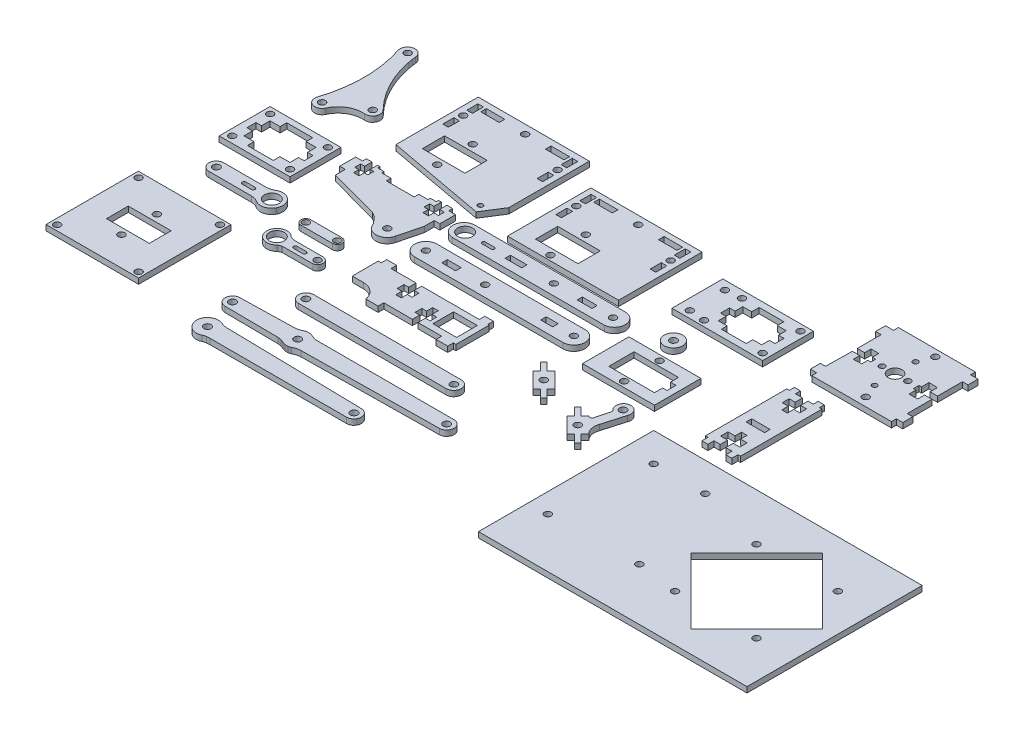
SolidWorks part; units mm, degrees
ref_plane "Front Plane" through (0, 0, 0) normal (0, 0, 1) x (1, 0, 0)
ref_plane "Top Plane" through (0, 0, 0) normal (0, 1, 0) x (1, 0, 0)
ref_plane "Right Plane" through (0, 0, 0) normal (1, 0, 0) x (0, 0, -1)
sketch "Sketch6" plane through (0, 0, -6.8736) normal (0, 1, 0) x (1, 0, 0)
  line L36 (172.3993, 17.524) -> (172.3993, 14.7799)
  line L37 (172.3993, 14.7799) -> (176.2794, 14.7799)
  line L38 (176.2794, 14.7799) -> (176.2794, 10.7799)
  line L39 (176.2794, 10.7799) -> (173.032, 10.7799)
  line L40 (173.032, 10.7799) -> (173.032, 7.063)
  line L41 (173.032, 7.063) -> (176.2794, 7.063)
  line L42 (176.2794, 7.063) -> (176.2794, 3.563)
  line L43 (176.2794, 3.563) -> (179.2794, 3.563)
  line L44 (179.2794, 3.563) -> (179.2794, 7.063)
  line L45 (179.2794, 7.063) -> (182.5439, 7.063)
  line L46 (182.5439, 7.063) -> (182.5439, 10.7799)
  line L47 (182.5439, 10.7799) -> (179.2794, 10.7799)
  line L48 (179.2794, 10.7799) -> (179.2794, 14.7799)
  line L49 (179.2794, 14.7799) -> (182.1277, 14.7799)
  line L50 (182.1277, 14.7799) -> (182.1277, 17.4216)
  line L54 (182.1277, -32.5784) -> (182.1277, -29.2201)
  line L55 (182.1277, -29.2201) -> (178.7635, -29.2201)
  line L56 (178.7635, -29.2201) -> (178.7635, -25.2201)
  line L57 (178.7635, -25.2201) -> (182.3404, -25.2201)
  line L58 (182.3404, -25.2201) -> (182.3404, -21.2526)
  line L59 (182.3404, -21.2526) -> (178.7635, -21.2526)
  line L60 (178.7635, -21.2526) -> (178.7635, -17.7526)
  line L61 (178.7635, -17.7526) -> (175.7635, -17.7526)
  line L62 (175.7635, -17.7526) -> (175.7635, -21.2526)
  line L63 (175.7635, -21.2526) -> (171.9828, -21.2526)
  line L64 (171.9828, -21.2526) -> (171.9828, -25.2201)
  line L65 (171.9828, -25.2201) -> (175.7635, -25.2201)
  line L66 (175.7635, -25.2201) -> (175.7635, -29.2201)
  line L67 (175.7635, -29.2201) -> (172.3993, -29.2201)
  line L68 (172.3993, -29.2201) -> (172.3993, -32.476)
  line L72 (172.2635, -8.7201) -> (182.2635, -8.7201)
  line L73 (182.2635, -8.7201) -> (182.2635, -11.7201)
  line L74 (182.2635, -11.7201) -> (172.2635, -11.7201)
  line L75 (172.2635, -11.7201) -> (172.2635, -8.7201)
  line L132 (186.7635, -29.2201) -> (185.3957, -29.2201)
  line L133 (185.3957, -29.2201) -> (185.3957, -32.5784)
  line L134 (167.7635, -29.2201) -> (169.1313, -29.2201)
  line L135 (169.1313, -29.2201) -> (169.1313, -32.476)
  line L136 (169.1313, 17.524) -> (169.1313, 14.7799)
  line L137 (169.1313, 14.7799) -> (167.7635, 14.7799)
  line L138 (185.3957, 17.4216) -> (185.3957, 14.7799)
  line L139 (185.3957, 14.7799) -> (186.7635, 14.7799)
  line L140 (167.7635, 14.7799) -> (167.7635, -29.2201)
  line L141 (169.1313, -32.476) -> (172.3993, -32.476)
  line L142 (182.1277, 17.4216) -> (185.3957, 17.4216)
  line L143 (186.7635, 14.7799) -> (186.7635, -29.2201)
  line L144 (185.3957, -32.5784) -> (182.1277, -32.5784)
  line L145 (169.1313, 17.524) -> (172.3993, 17.524)
  dimension "D6" = 1.3678
  dimension "D7" = 3.268
extrude "Boss-Extrude1" add sketch "Sketch6" along normal blind 3
sketch "Sketch12" plane through (0, 0, 0) normal (0, 1, 0) x (1, 0, 0)
  line L2 (6.7832, 13.9824) -> (88.1268, 13.9824)
  line L55 (6.1199, 2.1705) -> (88.7901, 2.1705)
  line L111 (69.455, 9.4201) -> (77.455, 9.4201)
  line L112 (69.455, 9.4201) -> (69.455, 6.6201)
  line L113 (69.455, 6.6201) -> (77.455, 6.6201)
  line L114 (77.455, 9.4201) -> (77.455, 6.6201)
  line L115 (30.455, 9.5201) -> (39.455, 9.5201)
  line L116 (30.455, 9.5201) -> (30.455, 6.6201)
  line L117 (30.455, 6.6201) -> (39.455, 6.6201)
  line L118 (39.455, 9.5201) -> (39.455, 6.6201)
  line L119 (17.455, 8.0462) -> (22.4277, 8.0462) construction
  line L120 (17.455, 8.9315) -> (22.4277, 8.9315)
  line L121 (17.455, 7.1609) -> (22.4277, 7.1609)
  arc A102 (6.7832, 13.9824) -> (6.1199, 2.1705) centre (6.7832, 8.0578) ccw
  arc A103 (88.1268, 13.9824) -> (88.7901, 2.1705) centre (88.1268, 8.0578) cw
  circle A104 centre (7.4627, 8.0462) radius 4
  circle A105 centre (87.455, 8.0201) radius 1.82
  circle A106 centre (55.455, 8.0201) radius 1.82
  arc A107 (17.455, 8.9315) -> (17.455, 7.1609) centre (17.455, 8.0462) ccw
  arc A108 (22.4277, 7.1609) -> (22.4277, 8.9315) centre (22.4277, 8.0462) ccw
  point P22 (19.9414, 8.0462)
  dimension "D1" = 3.64
  dimension "D3" = 3.64
  dimension "D4" = 8
extrude "Boss-Extrude3" add sketch "Sketch12" along normal blind 3 separate body
sketch "Sketch14" plane through (0, 0, 0) normal (0, 1, 0) x (1, 0, 0)
  line L0 (20.7129, 62.7973) -> (80.7867, 62.7973)
  line L1 (80.7867, 62.7973) -> (80.7867, 17.6847)
  line L2 (80.7867, 17.6847) -> (20.7129, 17.6847)
  line L3 (20.7129, 17.6847) -> (20.7129, 62.7973)
  line L4 (28.2425, 59.822) -> (38.2425, 59.822)
  line L5 (28.2425, 59.822) -> (28.2425, 56.822)
  line L6 (28.2425, 56.822) -> (38.2425, 56.822)
  line L7 (38.2425, 59.822) -> (38.2425, 56.822)
  line L8 (63.2425, 59.822) -> (73.2425, 59.822)
  line L9 (63.2425, 59.822) -> (63.2425, 56.822)
  line L10 (63.2425, 56.822) -> (73.2425, 56.822)
  line L11 (73.2425, 59.822) -> (73.2425, 56.822)
  line L12 (74.7425, 59.822) -> (77.7425, 59.822)
  line L13 (74.7425, 59.822) -> (74.7425, 53.822)
  line L14 (74.7425, 53.822) -> (77.7425, 53.822)
  line L15 (77.7425, 59.822) -> (77.7425, 53.822)
  line L16 (74.7425, 46.822) -> (77.7425, 46.822)
  line L17 (74.7425, 46.822) -> (74.7425, 40.822)
  line L18 (74.7425, 40.822) -> (77.7425, 40.822)
  line L19 (77.7425, 46.822) -> (77.7425, 40.822)
  line L20 (29.7425, 35.822) -> (52.7425, 35.822)
  line L21 (29.7425, 35.822) -> (29.7425, 23.822)
  line L22 (29.7425, 23.822) -> (52.7425, 23.822)
  line L23 (52.7425, 35.822) -> (52.7425, 23.822)
  line L24 (23.7425, 46.822) -> (26.7425, 46.822)
  line L25 (23.7425, 46.822) -> (23.7425, 40.822)
  line L26 (23.7425, 40.822) -> (26.7425, 40.822)
  line L27 (26.7425, 46.822) -> (26.7425, 40.822)
  line L28 (23.7425, 59.822) -> (26.7425, 59.822)
  line L29 (23.7425, 59.822) -> (23.7425, 53.822)
  line L30 (23.7425, 53.822) -> (26.7425, 53.822)
  line L31 (26.7425, 59.822) -> (26.7425, 53.822)
  circle A0 centre (50.7425, 58.322) radius 1.82
  circle A1 centre (41.2425, 39.4969) radius 1.82
  circle A2 centre (41.2425, 20.3569) radius 1.82
  circle A3 centre (76.2425, 50.322) radius 1.82
  circle A4 centre (25.2425, 50.322) radius 1.82
  dimension "D1" = 19.14
  dimension "D2" = 3.64
  dimension "D3" = 3.64
  dimension "D4" = 3.64
  dimension "D5" = 3.64
extrude "Boss-Extrude4" add sketch "Sketch14" along normal blind 3 separate body
sketch "Sketch18" plane through (0, 0, 0) normal (0, 1, 0) x (1, 0, 0)
  line L0 (-52.2788, 74.8705) -> (7.7767, 74.8705)
  line L1 (7.7767, 74.8705) -> (7.7767, 31.3788)
  line L2 (7.7767, 31.3788) -> (0.9291, 20.5522)
  line L3 (0.9291, 20.5522) -> (-52.2788, 30.361)
  line L4 (-52.2788, 30.361) -> (-52.2788, 74.8705)
  line L5 (-44.7078, 71.6303) -> (-34.7078, 71.6303)
  line L6 (-44.7078, 71.6303) -> (-44.7078, 68.6303)
  line L7 (-44.7078, 68.6303) -> (-34.7078, 68.6303)
  line L8 (-34.7078, 71.6303) -> (-34.7078, 68.6303)
  line L9 (-49.2078, 71.6303) -> (-46.2078, 71.6303)
  line L10 (-49.2078, 71.6303) -> (-49.2078, 65.6303)
  line L11 (-49.2078, 65.6303) -> (-46.2078, 65.6303)
  line L12 (-46.2078, 71.6303) -> (-46.2078, 65.6303)
  line L13 (-49.2078, 58.6303) -> (-46.2078, 58.6303)
  line L14 (-49.2078, 58.6303) -> (-49.2078, 52.6303)
  line L15 (-49.2078, 52.6303) -> (-46.2078, 52.6303)
  line L16 (-46.2078, 58.6303) -> (-46.2078, 52.6303)
  line L17 (-43.2078, 47.6303) -> (-20.2078, 47.6303)
  line L18 (-43.2078, 47.6303) -> (-43.2078, 35.6303)
  line L19 (-43.2078, 35.6303) -> (-20.2078, 35.6303)
  line L20 (-20.2078, 47.6303) -> (-20.2078, 35.6303)
  line L21 (-9.7078, 71.6303) -> (0.2922, 71.6303)
  line L22 (-9.7078, 71.6303) -> (-9.7078, 68.6303)
  line L23 (-9.7078, 68.6303) -> (0.2922, 68.6303)
  line L24 (0.2922, 71.6303) -> (0.2922, 68.6303)
  line L25 (1.7922, 71.6303) -> (4.7922, 71.6303)
  line L26 (1.7922, 71.6303) -> (1.7922, 65.6303)
  line L27 (1.7922, 65.6303) -> (4.7922, 65.6303)
  line L28 (4.7922, 71.6303) -> (4.7922, 65.6303)
  line L29 (1.7922, 58.6303) -> (4.7922, 58.6303)
  line L30 (1.7922, 58.6303) -> (1.7922, 52.6303)
  line L31 (1.7922, 52.6303) -> (4.7922, 52.6303)
  line L32 (4.7922, 58.6303) -> (4.7922, 52.6303)
  circle A0 centre (3.3054, 62.1514) radius 1.82
  circle A1 centre (-0.9558, 24.7244) radius 1.2998
  circle A2 centre (-31.7081, 32.1289) radius 1.82
  circle A3 centre (-31.6898, 51.2689) radius 1.82
  circle A4 centre (-47.7078, 62.1303) radius 1.82
  circle A5 centre (-22.2078, 70.1303) radius 1.82
  dimension "D1" = 3.64
  dimension "D2" = 19.14
sketch "Sketch20" plane through (0, 0, 0) normal (0, 1, 0) x (1, 0, 0)
  line L0 (-3.3445, 5.1376) -> (-6.3445, 5.1376)
  line L1 (-6.3445, -0.1855) -> (-9.5309, -12.7114)
  line L2 (-21.2346, -12.8672) -> (-24.3389, -9.2481)
  line L3 (-24.3389, -9.2481) -> (-27.0786, -7.6072)
  line L4 (-27.0786, -7.6072) -> (-54.3445, -0.2275)
  line L5 (-54.3445, -0.2275) -> (-54.3445, 5.0581)
  line L6 (-54.3445, 5.0581) -> (-57.3445, 5.0581)
  line L7 (-57.3445, 5.0581) -> (-57.3445, 13.6523)
  line L8 (-57.3445, 13.6523) -> (-53.6006, 13.6523)
  line L9 (-53.6006, 13.6523) -> (-53.6006, 15.7725)
  line L10 (-53.6006, 15.7725) -> (-50.5945, 15.7725)
  line L11 (-50.5945, 15.7725) -> (-50.5945, 11.7725)
  line L12 (-50.5945, 11.7725) -> (-52.7659, 11.7725)
  line L13 (-52.7659, 11.7725) -> (-52.7659, 8.6302)
  line L14 (-52.7659, 8.6302) -> (-50.5945, 8.6302)
  line L15 (-50.5945, 8.6302) -> (-50.5945, 5.7725)
  line L16 (-50.5945, 5.7725) -> (-47.5945, 5.7725)
  line L17 (-47.5945, 5.7725) -> (-47.5945, 8.6302)
  line L18 (-47.5945, 8.6302) -> (-45.6767, 8.6302)
  line L19 (-45.6767, 8.6302) -> (-45.6767, 11.7725)
  line L20 (-45.6767, 11.7725) -> (-47.5945, 11.7725)
  line L21 (-47.5945, 11.7725) -> (-47.5945, 15.7725)
  line L22 (-47.5945, 15.7725) -> (-46.26, 15.7725)
  line L23 (-46.26, 15.7725) -> (-46.26, 14.5225)
  line L24 (-46.26, 14.5225) -> (-42.8445, 14.5225)
  line L25 (-42.8445, 14.5225) -> (-42.8445, 13.2725)
  line L26 (-42.8445, 13.2725) -> (-37.8445, 13.2725)
  line L27 (-37.8445, 13.2725) -> (-37.8445, 10.7725)
  line L28 (-37.8445, 10.7725) -> (-22.8445, 10.7725)
  line L29 (-22.8445, 10.7725) -> (-22.8445, 13.2725)
  line L30 (-22.8445, 13.2725) -> (-17.8445, 13.2725)
  line L31 (-17.8445, 13.2725) -> (-17.8445, 14.5225)
  line L32 (-17.8445, 14.5225) -> (-14.6403, 14.5225)
  line L33 (-14.6403, 14.5225) -> (-14.6403, 15.7725)
  line L34 (-14.6403, 15.7725) -> (-13.0945, 15.7725)
  line L35 (-13.0945, 15.7725) -> (-13.0945, 11.7725)
  line L36 (-13.0945, 11.7725) -> (-15.4488, 11.7725)
  line L37 (-15.4488, 11.7725) -> (-15.4488, 8.6851)
  line L38 (-15.4488, 8.6851) -> (-13.0945, 8.6851)
  line L39 (-13.0945, 8.6851) -> (-13.0945, 5.7725)
  line L40 (-13.0945, 5.7725) -> (-10.0945, 5.7725)
  line L41 (-10.0945, 5.7725) -> (-10.0945, 8.6674)
  line L42 (-10.0945, 8.6674) -> (-7.5507, 8.6674)
  line L43 (-7.5507, 8.6674) -> (-7.5507, 11.7725)
  line L44 (-7.5507, 11.7725) -> (-10.0945, 11.7725)
  line L45 (-10.0945, 11.7725) -> (-10.0945, 15.7725)
  line L46 (-10.0945, 15.7725) -> (-7.0098, 15.7725)
  line L47 (-7.0098, 15.7725) -> (-7.0098, 13.684)
  line L48 (-7.0098, 13.684) -> (-3.3445, 13.6514)
  line L49 (-3.3445, 13.6514) -> (-3.3445, 5.1376)
  line L50 (-6.3445, 5.1376) -> (-6.3445, -0.1855)
  arc A0 (-9.5309, -12.7114) -> (-21.2346, -12.8672) centre (-15.4037, -11.2174) cw
  circle A1 centre (-15.3445, -11.2275) radius 1.82
  dimension "D1" = 3.64
sketch "Sketch22" plane through (0, 0, 0) normal (0, 1, 0) x (1, 0, 0)
  line L0 (-22.8304, -83.5062) -> (5.98, -82.8529)
  line L1 (18.5125, -82.749) -> (92.2578, -82.749)
  line L2 (92.3104, -90.7487) -> (18.5715, -91.7184)
  line L3 (6.0387, -91.7793) -> (-22.7778, -91.5049)
  arc A0 (5.98, -82.8529) -> (10.0623, -81.6918) centre (5.7889, -74.4239) ccw
  arc A1 (10.0623, -81.6918) -> (10.658, -81.4927) centre (10.8295, -82.9967) cw
  arc A2 (10.658, -81.4927) -> (11.2714, -81.3569) centre (10.3161, -78.495) ccw
  arc A3 (11.2714, -81.3569) -> (11.8955, -81.2861) centre (11.7502, -82.7912) cw
  arc A4 (11.8955, -81.2861) -> (12.5237, -81.2808) centre (12.1844, -78.2942) ccw
  arc A5 (12.5237, -81.2808) -> (13.1489, -81.3413) centre (12.6941, -82.7806) cw
  arc A6 (13.1489, -81.3413) -> (13.7644, -81.4668) centre (14.0525, -78.4818) ccw
  arc A7 (13.7644, -81.4668) -> (14.3634, -81.656) centre (13.6195, -82.9685) cw
  arc A8 (14.3634, -81.656) -> (14.9394, -81.9067) centre (15.8391, -79.0526) ccw
  arc A9 (14.9394, -81.9067) -> (15.6165, -82.2065) centre (13.9387, -85.0813) cw
  arc A10 (15.6165, -82.2065) -> (16.3185, -82.4423) centre (16.5367, -80.6298) ccw
  arc A11 (16.3185, -82.4423) -> (17.0393, -82.6122) centre (15.9213, -85.7415) cw
  arc A12 (17.0393, -82.6122) -> (17.7727, -82.7147) centre (17.6534, -80.8935) ccw
  arc A13 (17.7727, -82.7147) -> (18.5125, -82.749) centre (17.9898, -86.0281) cw
  arc A14 (92.2578, -82.749) -> (92.3104, -90.7487) centre (92.2578, -86.7491) cw
  arc A15 (18.5715, -91.7184) -> (14.4371, -92.8659) centre (18.6822, -100.1392) ccw
  arc A16 (14.4371, -92.8659) -> (13.8407, -93.0629) centre (13.6751, -91.5605) cw
  arc A17 (13.8407, -93.0629) -> (13.2269, -93.1965) centre (14.1702, -96.0538) ccw
  arc A18 (13.2269, -93.1965) -> (12.6025, -93.2652) centre (12.753, -91.7611) cw
  arc A19 (12.6025, -93.2652) -> (11.9743, -93.2682) centre (12.3027, -96.2616) ccw
  arc A20 (11.9743, -93.2682) -> (11.3493, -93.2055) centre (11.8094, -91.7654) cw
  arc A21 (11.3493, -93.2055) -> (10.7342, -93.0779) centre (10.4346, -96.0685) ccw
  arc A22 (10.7342, -93.0779) -> (10.1359, -92.8866) centre (10.8846, -91.5762) cw
  arc A23 (10.1359, -92.8866) -> (9.5608, -92.6338) centre (8.6482, -95.4904) ccw
  arc A24 (9.5608, -92.6338) -> (8.8936, -92.3352) centre (10.5595, -89.5075) cw
  arc A25 (8.8936, -92.3352) -> (8.202, -92.0988) centre (7.9736, -93.8967) ccw
  arc A26 (8.202, -92.0988) -> (7.4916, -91.9264) centre (8.615, -88.8472) cw
  arc A27 (7.4916, -91.9264) -> (6.7685, -91.8196) centre (6.8709, -93.6279) ccw
  arc A28 (6.7685, -91.8196) -> (6.0387, -91.7793) centre (6.5832, -88.5467) cw
  arc A29 (-22.7778, -91.5049) -> (-22.8304, -83.5062) centre (-22.7397, -87.5052) cw
  circle A30 centre (-22.7398, -87.5051) radius 1.925
  circle A31 centre (12.2595, -87.275) radius 1.925
  circle A32 centre (92.2578, -86.749) radius 1.925
  dimension "D1" = 3.85
  dimension "D2" = 3.85
sketch "Sketch23" plane through (0, 0, 0) normal (0, 1, 0) x (1, 0, 0)
  line L0 (62.0938, -102.6123) -> (-12.185, -101.1529)
  line L1 (62.0145, -110.6115) -> (-11.7091, -110.5993)
  arc A0 (-18.7722, -99.8781) -> (-23.9525, -106.2408) centre (-18.181, -105.6496) ccw
  arc A1 (-23.9525, -106.2408) -> (-20.8301, -111.1061) centre (-17.5842, -105.5884) ccw
  arc A2 (-20.8301, -111.1061) -> (-15.5368, -111.3053) centre (-17.9986, -106.2928) ccw
  arc A3 (-15.5368, -111.3053) -> (-13.6142, -110.7239) centre (-12.8064, -116.8649) cw
  arc A4 (-13.6142, -110.7239) -> (-11.7091, -110.5993) centre (-11.7115, -125.1879) cw
  arc A5 (-18.7722, -99.8781) -> (-14.8108, -100.6548) centre (-18.0664, -106.7687) cw
  arc A6 (-14.8108, -100.6548) -> (-13.5188, -101.0143) centre (-13.353, -97.9172) ccw
  arc A7 (-13.5188, -101.0143) -> (-12.185, -101.1529) centre (-14.2348, -114.3916) cw
  arc A8 (62.0938, -102.6123) -> (62.0145, -110.6115) centre (62.0152, -106.6115) cw
  circle A9 centre (62.0152, -106.6115) radius 1.925
  circle A10 centre (-17.9809, -105.8257) radius 1.925
  dimension "D1" = 3.85
  dimension "D2" = 3.85
sketch "Sketch24" plane through (0, 0, 0) normal (0, 1, 0) x (1, 0, 0)
  line L0 (-90.2893, -24.7085) -> (-67.8284, -24.7085)
  line L1 (-90.2954, -32.7085) -> (-67.194, -32.744)
  line L2 (-75.2787, -28.7329) -> (-70.3703, -28.7329) construction
  line L3 (-75.2787, -27.7198) -> (-70.3703, -27.7198)
  line L4 (-75.2787, -29.7461) -> (-70.3703, -29.7461)
  arc A0 (-67.8284, -24.7085) -> (-62.5705, -23.1591) centre (-67.8284, -15.0125) ccw
  arc A1 (-62.5705, -23.1591) -> (-54.9836, -31.523) centre (-60.3229, -28.7434) cw
  arc A2 (-54.9836, -31.523) -> (-63.9473, -33.5823) centre (-60.343, -28.7329) cw
  arc A3 (-67.194, -32.744) -> (-63.9473, -33.5823) centre (-67.2043, -39.4905) cw
  arc A4 (-75.2787, -27.7198) -> (-75.2787, -29.7461) centre (-75.2787, -28.7329) ccw
  arc A5 (-70.3703, -29.7461) -> (-70.3703, -27.7198) centre (-70.3703, -28.7329) ccw
  circle A6 centre (-90.2893, -28.7085) radius 1.925
  circle A7 centre (-60.2893, -28.7085) radius 4
  arc A8 (-90.2954, -32.7085) -> (-90.2893, -24.7085) centre (-90.2893, -28.7085) cw
  point P13 (-72.8245, -28.7329)
  dimension "D1" = 3.85
  dimension "D2" = 8
sketch "Sketch26" plane through (0, 0, 0) normal (0, 1, 0) x (1, 0, 0)
  line L0 (-87.7528, 74.718) -> (-87.4104, 72.6313)
  line L1 (-87.7528, 74.718) -> (-88.0164, 76.816)
  arc A0 (-88.0164, 76.816) -> (-95.8236, 75.1147) centre (-92.0067, 76.3629) ccw
  arc A1 (-95.8236, 75.1147) -> (-95.7872, 31.4073) centre (-162.8228, 53.2052) cw
  arc A2 (-95.7872, 31.4073) -> (-88.3346, 28.5226) centre (-91.9816, 30.1698) ccw
  arc A3 (-88.3346, 28.5226) -> (-75.123, 36.3095) centre (-76.205, 23.044) cw
  arc A4 (-75.123, 36.3095) -> (-71.9331, 43.1193) centre (-74.7969, 40.3087) ccw
  arc A5 (-71.9331, 43.1193) -> (-87.4104, 72.6313) centre (-30.7636, 83.5248) cw
  circle A6 centre (-74.764, 40.2933) radius 1.82
  circle A7 centre (-91.9939, 30.1381) radius 1.82
  circle A8 centre (-91.9939, 76.3923) radius 1.82
  dimension "D1" = 3.64
  dimension "D2" = 3.64
  dimension "D3" = 3.64
sketch "Sketch27" plane through (0, 0, 0) normal (0, 1, 0) x (1, 0, 0)
  line L0 (-91.9831, 11.0737) -> (-77.9831, 11.0737)
  line L1 (-104.1231, 14.1616) -> (-65.8431, 14.1616)
  line L2 (-104.1231, 14.1616) -> (-104.1231, -13.3284)
  line L3 (-104.1231, -13.3284) -> (-65.8431, -13.3284)
  line L4 (-65.8431, 14.1616) -> (-65.8431, -13.3284)
  line L5 (-77.9831, 11.0737) -> (-77.9831, 7.4737)
  line L6 (-77.9831, 7.4737) -> (-72.5331, 7.4737)
  line L7 (-72.5331, 7.4737) -> (-72.5331, 2.8437)
  line L8 (-69.5331, 2.8437) -> (-69.5331, -2.0063)
  line L9 (-69.5331, -2.0063) -> (-72.5331, -2.0063)
  line L10 (-72.5331, -2.0063) -> (-72.5331, -6.6363)
  line L11 (-72.5331, -6.6363) -> (-77.9831, -6.6363)
  line L12 (-77.9831, -6.6363) -> (-77.9831, -10.2363)
  line L13 (-77.9831, -10.2363) -> (-91.9831, -10.2363)
  line L14 (-91.9831, -10.2363) -> (-91.9831, -6.6384)
  line L15 (-91.9831, -6.6384) -> (-97.4331, -6.6384)
  line L16 (-97.4331, -6.6384) -> (-97.4331, -2.0084)
  line L17 (-97.4331, -2.0084) -> (-100.4331, -2.0084)
  line L18 (-100.4331, -2.0084) -> (-100.4331, 2.8416)
  line L19 (-100.4331, 2.8416) -> (-97.4331, 2.8416)
  line L20 (-97.4331, 2.8416) -> (-97.4331, 7.4716)
  line L21 (-97.4331, 7.4716) -> (-91.9831, 7.4716)
  line L22 (-91.9831, 7.4716) -> (-91.9831, 11.0737)
  line L23 (-72.5331, 2.8437) -> (-69.5331, 2.8437)
  circle A0 centre (-100.6231, 10.6616) radius 1.82
  circle A1 centre (-100.6231, -9.8284) radius 1.82
  circle A2 centre (-69.3431, -9.8263) radius 1.82
  circle A3 centre (-69.3431, 10.6616) radius 1.82
  dimension "D1" = 3.64
  dimension "D2" = 14
  dimension "D3" = 3.6
  dimension "D4" = 3.6
  dimension "D5" = 4.85
  dimension "D6" = 4.63
  dimension "D7" = 3.19
  dimension "D8" = 3.19
  dimension "D9" = 3.19
  dimension "D10" = 5.45
  dimension "D11" = 3
  dimension "D12" = 3.19
  dimension "D13" = 3.19
  dimension "D14" = 3.19
  dimension "D15" = 3.5
  dimension "D16" = 3.5
  dimension "D17" = 3.5
sketch "Sketch28" plane through (0, 0, 0) normal (0, 1, 0) x (1, 0, 0)
  line L0 (109.0997, -2.2732) -> (133.1497, -2.2732)
  line L1 (100.7124, 3.3321) -> (139.6281, 3.3321)
  line L2 (100.7124, 3.3321) -> (100.7124, -21.7433)
  line L3 (100.7124, -21.7433) -> (139.6281, -21.7433)
  line L4 (139.6281, 3.3321) -> (139.6281, -21.7433)
  line L5 (133.1497, -2.2732) -> (133.1497, -6.6732)
  line L6 (133.1497, -6.6732) -> (136.1497, -6.6732)
  line L7 (136.1497, -6.6732) -> (136.1497, -11.5232)
  line L8 (136.1497, -11.5232) -> (133.7949, -11.5232)
  line L9 (133.7949, -11.5232) -> (133.7949, -15.9232)
  line L10 (133.7949, -15.9232) -> (109.0997, -15.9232)
  line L11 (109.0997, -15.9232) -> (109.0997, -2.2732)
  circle A0 centre (120.2396, 0.384) radius 1.82
  circle A1 centre (120.2396, -18.756) radius 1.82
  dimension "D1" = 3.64
  dimension "D2" = 3.64
  dimension "D3" = 3
  dimension "D4" = 24.05
  dimension "D5" = 4.85
  dimension "D6" = 4.4
  dimension "D7" = 19.14
sketch "Sketch29" plane through (0, 0, 0) normal (0, 1, 0) x (1, 0, 0)
  line L0 (122.1756, 52.3026) -> (135.5756, 52.3026)
  line L1 (98.979, 55.8405) -> (147.9656, 55.8405)
  line L2 (98.979, 55.8405) -> (98.979, 28.3505)
  line L3 (98.979, 28.3505) -> (147.9656, 28.3505)
  line L4 (147.9656, 55.8405) -> (147.9656, 28.3505)
  line L5 (135.5756, 52.3026) -> (135.5756, 48.7026)
  line L6 (135.5756, 48.7026) -> (140.3756, 48.7026)
  line L7 (140.3756, 48.7026) -> (140.3756, 44.5226)
  line L8 (143.3756, 44.5226) -> (143.3756, 39.6726)
  line L9 (143.3756, 39.6726) -> (140.3756, 39.6726)
  line L10 (140.3756, 39.6726) -> (140.3756, 35.4926)
  line L11 (140.3756, 35.4926) -> (135.5756, 35.4926)
  line L12 (135.5756, 35.4926) -> (135.5756, 31.8926)
  line L13 (135.5756, 31.8926) -> (122.1756, 31.8926)
  line L14 (122.1756, 31.8926) -> (122.1756, 35.0385)
  line L15 (122.1756, 35.0385) -> (117.3756, 35.0385)
  line L16 (117.3756, 35.0385) -> (117.3756, 39.2185)
  line L17 (117.3756, 39.2185) -> (114.3756, 39.2185)
  line L18 (114.3756, 39.2185) -> (114.3756, 44.0726)
  line L19 (114.3756, 44.0726) -> (117.3756, 44.0726)
  line L20 (117.3756, 44.0726) -> (117.3756, 48.2526)
  line L21 (117.3756, 48.2526) -> (122.1756, 48.2526)
  line L22 (122.1756, 48.2526) -> (122.1756, 52.3026)
  line L23 (140.3756, 44.5226) -> (143.3756, 44.5226)
  circle A0 centre (113.2856, 51.8905) radius 1.82
  circle A1 centre (113.2856, 31.4005) radius 1.82
  circle A2 centre (144.4656, 31.8547) radius 1.82
  circle A3 centre (144.4656, 52.3405) radius 1.82
  circle A4 centre (104.8061, 51.1467) radius 1.82
  circle A5 centre (104.8302, 32.1467) radius 1.82
  point P72 (0, 0)
  point P73 (107.068, 31.8505)
  dimension "D1" = 3.64
  dimension "D35" = 3.6379
  dimension "D2" = 13.4
  dimension "D3" = 3.6
  dimension "D4" = 3.6
  dimension "D5" = 4.85
  dimension "D6" = 4.18
  dimension "D7" = 4.09
  dimension "D8" = 3.6379
  dimension "D9" = 4.09
  dimension "D10" = 4.8
  dimension "D11" = 3
  dimension "D12" = 4.09
  dimension "D13" = 3.6379
  dimension "D14" = 4.09
  dimension "D15" = 3.5
  dimension "D16" = 3.5
  dimension "D17" = 19
  dimension "D36" = 3.6379
  dimension "D37" = 3.6379
sketch "Sketch30" plane through (0, 0, 0) normal (0, 1, 0) x (1, 0, 0)
  line L0 (17.989, -28.9872) -> (4.4448, -28.9872)
  line L1 (11.9231, -50.0571) -> (18.5165, -50.0571)
  line L2 (18.5165, -50.0571) -> (18.5165, -46.9872)
  line L3 (18.5165, -46.9872) -> (33.989, -46.9872)
  line L4 (33.989, -46.9872) -> (33.989, -42.9872)
  line L5 (33.989, -42.9872) -> (31.4392, -42.9872)
  line L6 (31.4392, -42.9872) -> (31.4392, -39.3422)
  line L7 (31.4392, -39.3422) -> (33.989, -39.3422)
  line L8 (33.989, -39.3422) -> (33.989, -35.9872)
  line L9 (33.989, -35.9872) -> (36.989, -35.9872)
  line L10 (36.989, -35.9872) -> (36.989, -39.3774)
  line L11 (36.989, -39.3774) -> (39.5388, -39.3774)
  line L12 (39.5388, -39.3774) -> (39.5388, -42.9872)
  line L13 (39.5388, -42.9872) -> (36.989, -42.9872)
  line L14 (36.989, -42.9872) -> (36.989, -46.9872)
  line L15 (36.989, -46.9872) -> (49.8067, -46.9872)
  line L16 (49.8067, -46.9872) -> (49.8067, -49.9872)
  line L17 (52.1127, -25.9872) -> (52.1127, -28.9872)
  line L18 (52.1127, -28.9872) -> (20.989, -28.9872)
  line L19 (20.989, -28.9872) -> (20.989, -32.9872)
  line L20 (20.989, -32.9872) -> (23.539, -32.9872)
  line L21 (23.539, -32.9872) -> (23.539, -36.7505)
  line L22 (23.539, -36.7505) -> (20.989, -36.7505)
  line L23 (20.989, -36.7505) -> (20.989, -39.9872)
  line L24 (20.989, -39.9872) -> (17.989, -39.9872)
  line L25 (17.989, -39.9872) -> (17.989, -36.6921)
  line L26 (17.989, -36.6921) -> (15.439, -36.6921)
  line L27 (15.439, -36.6921) -> (15.439, -32.9872)
  line L28 (15.439, -32.9872) -> (17.989, -32.9872)
  line L29 (17.989, -32.9872) -> (17.989, -28.9872)
  line L30 (4.4448, -28.9872) -> (4.4448, -25.9872)
  line L31 (41.6011, -32.3441) -> (54.4301, -32.3441)
  line L32 (41.6011, -32.3441) -> (41.6011, -43.5339)
  line L33 (41.6011, -43.5339) -> (54.4301, -43.5339)
  line L34 (54.4301, -32.3441) -> (54.4301, -43.5339)
  line L35 (-2.511, -42.9872) -> (3.489, -42.9872)
  line L36 (-0.8977, -25.9872) -> (-0.8977, -28.9872)
  line L37 (-0.8977, -28.9872) -> (-2.511, -28.9872)
  line L38 (56.0898, -49.9872) -> (56.0898, -46.9872)
  line L39 (56.0898, -46.9872) -> (57.489, -46.9872)
  line L40 (56.7962, -25.9872) -> (56.7962, -28.9872)
  line L41 (56.7962, -28.9872) -> (57.489, -28.9872)
  line L42 (57.489, -28.9872) -> (57.489, -46.9872)
  line L43 (56.0898, -49.9872) -> (49.8067, -49.9872)
  line L44 (56.7962, -25.9872) -> (52.1127, -25.9872)
  line L45 (-0.8977, -25.9872) -> (4.4448, -25.9872)
  line L46 (-2.511, -42.9872) -> (-2.511, -28.9872)
  arc A0 (3.489, -42.9872) -> (11.9231, -50.0571) centre (3.489, -51.5529) cw
  dimension "D1" = 3.645
  dimension "D2" = 2.5498
  dimension "D3" = 2.55
  dimension "D4" = 2.55
  dimension "D5" = 2.55
  dimension "D6" = 2.55
sketch "Sketch31" plane through (0, 0, 0) normal (0, 1, 0) x (1, 0, 0)
  line L0 (-40.1799, -27.8411) -> (-23.1799, -27.8411)
  line L1 (-23.1799, -33.0411) -> (-40.1799, -33.0411)
  arc A0 (-23.1799, -27.8411) -> (-23.1799, -33.0411) centre (-23.1799, -30.4411) cw
  arc A1 (-40.1799, -33.0411) -> (-40.1799, -27.8411) centre (-40.1799, -30.4411) cw
  circle A2 centre (-40.1799, -30.4411) radius 1.82
  circle A3 centre (-23.1799, -30.4411) radius 1.82
  dimension "D1" = 3.64
  dimension "D2" = 3.64
  dimension "D3" = 2.6
  dimension "D4" = 2.6
  dimension "D5" = 2.6
sketch "Sketch32" plane through (0, 0, 0) normal (0, 1, 0) x (1, 0, 0)
  line L0 (-19.3691, -41.9276) -> (-34.5684, -41.9276)
  line L1 (-18.8998, -47.8907) -> (-35.1542, -47.962)
  line L2 (-35.1542, -47.962) -> (-35.7319, -48.0649)
  line L3 (-31.4441, -44.9276) -> (-26.3849, -44.9276) construction
  line L4 (-31.4441, -43.9544) -> (-26.3849, -43.9544)
  line L5 (-31.4441, -45.9008) -> (-26.3849, -45.9008)
  arc A0 (-34.5684, -41.9276) -> (-38.333, -40.3416) centre (-34.5684, -36.6667) cw
  arc A1 (-38.333, -40.3416) -> (-42.1025, -50.3785) centre (-41.3099, -44.9499) ccw
  arc A2 (-42.1025, -50.3785) -> (-37.3382, -48.7649) centre (-41.3026, -44.9) ccw
  arc A3 (-37.3382, -48.7649) -> (-36.8315, -48.4691) centre (-36.5499, -49.5334) cw
  arc A4 (-36.8315, -48.4691) -> (-35.7319, -48.0649) centre (-38.4338, -42.4122) ccw
  arc A5 (-19.3691, -41.9276) -> (-18.8998, -47.8907) centre (-19.3691, -44.9276) cw
  arc A6 (-31.4441, -43.9544) -> (-31.4441, -45.9008) centre (-31.4441, -44.9276) ccw
  arc A7 (-26.3849, -45.9008) -> (-26.3849, -43.9544) centre (-26.3849, -44.9276) ccw
  circle A8 centre (-41.3691, -44.9276) radius 4
  circle A9 centre (-19.3691, -44.9276) radius 1.82
  point P17 (-28.9145, -44.9276)
  dimension "D1" = 3.64
sketch "Sketch33" plane through (0, 0, 0) normal (0, 1, 0) x (1, 0, 0)
  line L0 (-4.2145, -66.2122) -> (75.574, -66.2122) construction
  line L1 (-4.2145, -62.1261) -> (75.574, -62.1261)
  line L2 (-4.2145, -70.2983) -> (75.574, -70.2983)
  arc A0 (-4.2145, -62.1261) -> (-4.2145, -70.2983) centre (-4.2145, -66.2122) ccw
  arc A1 (75.574, -70.2983) -> (75.574, -62.1261) centre (75.574, -66.2122) ccw
  circle A2 centre (-4.3278, -66.2456) radius 1.87
  circle A3 centre (75.6722, -66.2456) radius 1.87
  point P2 (35.6798, -66.2122)
  dimension "D1" = 3.74
  dimension "D2" = 3.74
sketch "Sketch34" plane through (0, 0, 0) normal (0, 1, 0) x (1, 0, 0)
  line L0 (85.46, -5.1233) -> (5.46, -5.1233)
  line L1 (5.3693, -17.1401) -> (85.46, -17.1233)
  line L2 (85.46, -17.1401) -> (85.46, -17.1233)
  line L3 (15.46, -9.6233) -> (22.96, -9.6233)
  line L4 (15.46, -9.6233) -> (15.46, -12.6233)
  line L5 (15.46, -12.6233) -> (22.96, -12.6233)
  line L6 (22.96, -9.6233) -> (22.96, -12.6233)
  line L7 (68.9695, -9.6233) -> (75.46, -9.6233)
  line L8 (68.9695, -9.6233) -> (68.9695, -12.6233)
  line L9 (68.9695, -12.6233) -> (75.46, -12.6233)
  line L10 (75.46, -9.6233) -> (75.46, -12.6233)
  arc A0 (5.46, -5.1233) -> (5.3693, -17.1401) centre (5.4147, -11.1317) ccw
  arc A1 (85.46, -5.1233) -> (85.46, -17.1401) centre (85.46, -11.1317) cw
  circle A2 centre (85.46, -11.1233) radius 1.82
  circle A3 centre (37.46, -11.1233) radius 1.82
  circle A4 centre (5.46, -11.1233) radius 1.82
  dimension "D1" = 3.64
  dimension "D2" = 3.64
  dimension "D3" = 3.64
sketch "Sketch35" plane through (0, 0, 0) normal (0, 1, 0) x (1, 0, 0)
  circle A0 centre (114.4508, 13.6733) radius 1.925
  circle A1 centre (114.4508, 13.6733) radius 5
  dimension "D1" = 3.85
sketch "Sketch36" plane through (0, 0, 0) normal (0, 1, 0) x (1, 0, 0)
  line L0 (96.6735, -32.7093) -> (105.1588, -41.1946)
  line L1 (105.1588, -41.1946) -> (103.0375, -43.3159)
  line L2 (103.0375, -43.3159) -> (107.2801, -47.5586)
  line L3 (107.2801, -47.5586) -> (105.583, -49.2556)
  line L4 (105.583, -49.2556) -> (101.3404, -45.013)
  line L5 (101.3404, -45.013) -> (99.2191, -47.1343)
  line L6 (99.2191, -47.1343) -> (90.7338, -38.6491)
  line L7 (90.7338, -38.6491) -> (92.8551, -36.5277)
  line L8 (92.8551, -36.5277) -> (88.6125, -32.2851)
  line L9 (88.6125, -32.2851) -> (90.3095, -30.588)
  line L10 (90.3095, -30.588) -> (94.5522, -34.8307)
  line L11 (94.5522, -34.8307) -> (96.6735, -32.7093)
  circle A0 centre (97.9463, -39.9218) radius 1.82
  dimension "D1" = 3.64
sketch "Sketch37" plane through (0, 0, 0) normal (0, 1, 0) x (1, 0, 0)
  line L0 (135.4169, -53.0651) -> (133.2956, -55.1864)
  line L1 (133.2956, -55.1864) -> (137.5382, -59.4291)
  line L2 (137.5382, -59.4291) -> (135.8412, -61.1261)
  line L3 (135.8412, -61.1261) -> (131.5985, -56.8835)
  line L4 (131.5985, -56.8835) -> (129.4772, -59.0048)
  line L5 (129.4772, -59.0048) -> (120.9919, -50.5195)
  line L6 (120.9919, -50.5195) -> (123.1132, -48.3982)
  line L7 (123.1132, -48.3982) -> (118.8706, -44.1556)
  line L8 (118.8706, -44.1556) -> (120.5677, -42.4585)
  line L9 (120.5677, -42.4585) -> (124.8103, -46.7012)
  line L10 (124.8103, -46.7012) -> (126.9316, -44.5798)
  line L11 (129.1898, -43.6445) -> (131.0313, -36.7977)
  line L12 (133.7199, -45.6405) -> (137.1051, -33.9217)
  line L13 (131.0313, -36.7977) -> (131.0313, -35.5609)
  arc A0 (126.9316, -44.5798) -> (129.1898, -43.6445) centre (127.867, -43.6445) ccw
  arc A1 (135.4169, -53.0651) -> (133.7199, -45.6405) centre (140.4805, -48.0015) cw
  circle A2 centre (133.3808, -32.4738) radius 1.925
  arc A3 (137.1051, -33.9217) -> (131.0313, -35.5609) centre (133.4056, -32.2861) ccw
  circle A4 centre (128.2044, -51.7923) radius 1.8201
  dimension "D1" = 3.6402
  dimension "D2" = 3.85
sketch "Sketch38" plane through (0, 0, 0) normal (0, 1, 0) x (1, 0, 0)
  line L0 (214.8986, 72.4925) -> (211.8986, 72.4925)
  line L1 (211.8986, 72.4925) -> (211.8986, 59.0158)
  line L2 (211.8986, 59.0158) -> (207.8986, 59.0158)
  line L3 (207.8986, 59.0158) -> (207.8986, 62.9131)
  line L4 (207.8986, 62.9131) -> (203.2662, 63.0537)
  line L5 (203.2662, 63.0537) -> (203.2662, 59.0158)
  line L6 (203.2662, 59.0158) -> (201.8986, 59.0158)
  line L7 (201.8986, 59.0158) -> (201.8986, 56.0158)
  line L8 (201.8986, 56.0158) -> (203.2651, 56.0158)
  line L9 (203.2651, 56.0158) -> (203.2651, 52.2449)
  line L10 (203.2651, 52.2449) -> (207.8986, 52.2911)
  line L11 (207.8986, 52.2911) -> (207.8986, 56.0158)
  line L12 (207.8986, 56.0158) -> (211.8986, 56.0158)
  line L13 (211.8986, 56.0158) -> (211.8986, 42.6429)
  line L14 (211.8986, 42.6429) -> (214.8986, 42.6429)
  line L15 (164.8986, 42.6429) -> (167.6736, 42.6429)
  line L16 (167.8986, 56.962) -> (171.8986, 56.962)
  line L17 (171.8986, 56.962) -> (171.8986, 53.4656)
  line L18 (171.8986, 53.4656) -> (176.3141, 53.6437)
  line L19 (176.3141, 53.6437) -> (176.3141, 56.962)
  line L20 (176.3141, 56.962) -> (177.8986, 56.962)
  line L21 (177.8986, 56.962) -> (177.8986, 59.6133)
  line L22 (177.8986, 59.6133) -> (176.1034, 59.6133)
  line L23 (176.1034, 59.6133) -> (176.1034, 63.1125)
  line L24 (176.1034, 63.1125) -> (171.8986, 63.1125)
  line L25 (171.8986, 63.1125) -> (171.8986, 59.6133)
  line L26 (171.8986, 59.6133) -> (167.8986, 59.6133)
  line L27 (167.8986, 59.6133) -> (167.8986, 72.4925)
  line L28 (167.8986, 72.4925) -> (164.8986, 72.4925)
  line L29 (167.6736, 42.6429) -> (167.8986, 56.962)
  line L30 (214.8986, 37.2429) -> (211.4066, 37.2429)
  line L31 (211.4066, 37.2429) -> (211.4066, 34.6032)
  line L32 (164.8986, 37.2429) -> (168.3401, 37.2429)
  line L33 (168.3401, 37.2429) -> (168.3401, 34.6032)
  line L34 (214.8986, 37.2429) -> (214.8986, 42.6429)
  line L35 (211.4066, 34.6032) -> (168.3401, 34.6032)
  line L36 (164.8986, 37.2429) -> (164.8986, 42.6429)
  line L37 (210.8826, 80.5322) -> (210.8826, 77.8925)
  line L38 (210.8826, 77.8925) -> (214.8986, 77.8925)
  line L39 (164.8986, 77.8925) -> (169.2475, 77.8925)
  line L40 (169.2475, 77.8925) -> (169.2475, 80.5322)
  line L41 (169.2475, 80.5322) -> (210.8826, 80.5322)
  line L42 (164.8986, 77.8925) -> (164.8986, 72.4925)
  line L43 (214.8986, 72.4925) -> (214.8986, 77.8925)
  circle A0 centre (189.8986, 58.0322) radius 3.75
  circle A1 centre (182.8986, 58.0322) radius 1.5333
  circle A2 centre (189.889, 69.1146) radius 1.4239
  circle A3 centre (196.8493, 58.0203) radius 1.6482
  circle A4 centre (192.8986, 76.7822) radius 1.82
  circle A5 centre (189.8986, 47.0381) radius 1.3524
  circle A6 centre (192.885, 39.1928) radius 1.82
  dimension "D6" = 3.64
  dimension "D7" = 3.64
  dimension "D1" = 5.4
  dimension "D2" = 5.4
  dimension "D3" = 5.4
  dimension "D4" = 5.4
  dimension "D5" = 2.6397
extrude "Boss-Extrude5" add sketch "Sketch18" along normal blind 3 separate body
extrude "Boss-Extrude6" add sketch "Sketch38" along normal blind 3 separate body
extrude "Boss-Extrude7" add sketch "Sketch37" along normal blind 3 separate body
extrude "Boss-Extrude8" add sketch "Sketch36" along normal blind 3 separate body
extrude "Boss-Extrude9" add sketch "Sketch35" along normal blind 3 separate body
extrude "Boss-Extrude10" add sketch "Sketch34" along normal blind 3 separate body
extrude "Boss-Extrude11" add sketch "Sketch33" along normal blind 3 separate body
extrude "Boss-Extrude12" add sketch "Sketch32" along normal blind 3 separate body
extrude "Boss-Extrude13" add sketch "Sketch31" along normal blind 3 separate body
extrude "Boss-Extrude14" add sketch "Sketch30" along normal blind 3 separate body
extrude "Boss-Extrude15" add sketch "Sketch29" along normal blind 3 separate body
extrude "Boss-Extrude16" add sketch "Sketch28" along normal blind 3 separate body
extrude "Boss-Extrude17" add sketch "Sketch27" along normal blind 3 separate body
extrude "Boss-Extrude18" add sketch "Sketch26" along normal blind 3 separate body
extrude "Boss-Extrude19" add sketch "Sketch24" along normal blind 3 separate body
extrude "Boss-Extrude20" add sketch "Sketch23" along normal blind 3 separate body
extrude "Boss-Extrude21" add sketch "Sketch22" along normal blind 3 separate body
extrude "Boss-Extrude22" add sketch "Sketch20" along normal blind 3 separate body
sketch "Sketch41" plane through (0, 0, 0) normal (0, 1, 0) x (1, 0, 0)
  line L0 (218.7805, -81.1114) -> (254.3702, -116.7011)
  line L1 (151.2617, -33.8089) -> (296.4281, -33.8089)
  line L2 (151.2617, -33.8089) -> (151.2617, -128.5401)
  line L3 (151.2617, -128.5401) -> (296.4281, -128.5401)
  line L4 (296.4281, -33.8089) -> (296.4281, -128.5401)
  line L5 (254.3702, -116.7011) -> (289.8339, -81.2374)
  line L6 (289.8339, -81.2374) -> (254.2442, -45.6477)
  line L7 (254.2442, -45.6477) -> (218.7805, -81.1114)
  circle A0 centre (232.313, -59.3089) radius 1.82
  circle A1 centre (194.813, -49.5089) radius 1.82
  circle A2 centre (166.913, -49.5089) radius 1.82
  circle A3 centre (161.813, -101.6089) radius 1.82
  circle A4 centre (210.013, -100.3089) radius 1.82
  circle A5 centre (232.313, -103.3089) radius 1.82
  circle A6 centre (276.313, -103.3089) radius 1.82
  circle A7 centre (276.313, -59.3089) radius 1.82
  dimension "D1" = 3.64
extrude "Boss-Extrude23" add sketch "Sketch41" along normal blind 3 separate body
sketch "Sketch42" plane through (0, 0, 0) normal (0, 1, 0) x (1, 0, 0)
  line L0 (-109.4446, -51.7385) -> (-59.3919, -51.7385)
  line L1 (-109.4446, -51.7385) -> (-109.4446, -101.6556)
  line L2 (-109.4446, -101.6556) -> (-59.3919, -101.6556)
  line L3 (-59.3919, -51.7385) -> (-59.3919, -101.6556)
  line L4 (-95.8417, -82.5662) -> (-72.6942, -82.5662)
  line L5 (-95.8417, -82.5662) -> (-95.8417, -70.7669)
  line L6 (-95.8417, -70.7669) -> (-72.6942, -70.7669)
  line L7 (-72.6942, -82.5662) -> (-72.6942, -70.7669)
  circle A0 centre (-106.3103, -54.7462) radius 1.82
  circle A1 centre (-84.3064, -66.8836) radius 1.82
  circle A2 centre (-62.3037, -54.735) radius 1.82
  circle A3 centre (-84.3093, -86.0236) radius 1.82
  circle A4 centre (-62.3053, -98.732) radius 1.82
  circle A5 centre (-106.3086, -98.7412) radius 1.82
  dimension "D1" = 19.14
  dimension "D2" = 3.64
extrude "Boss-Extrude24" add sketch "Sketch42" along normal blind 3 separate body
